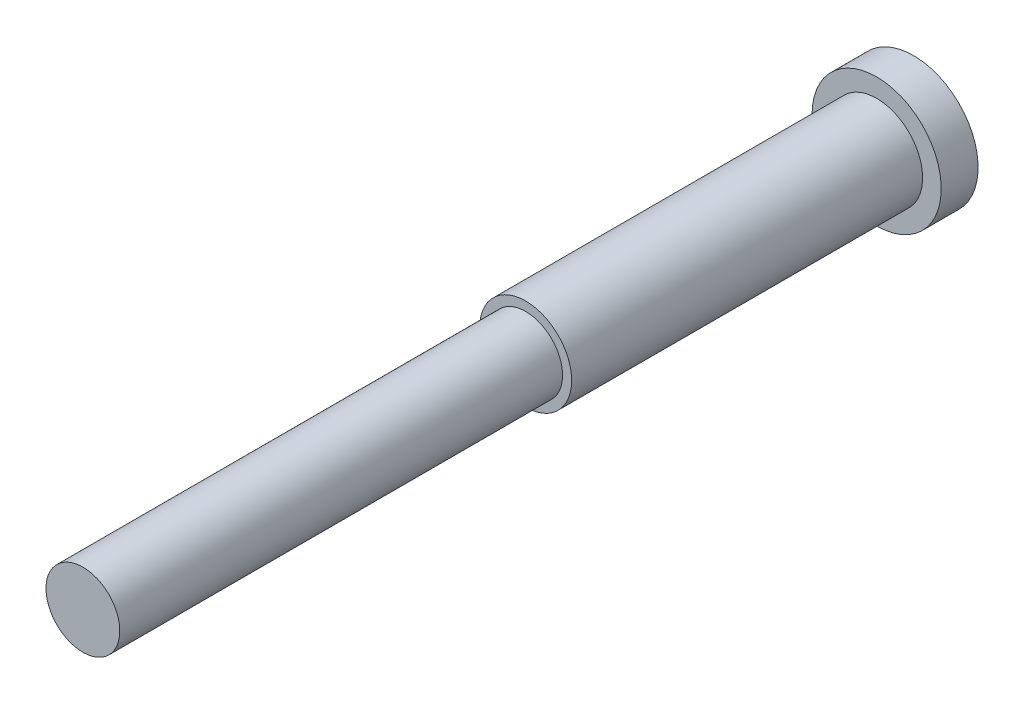
SolidWorks part; units mm, degrees
material "PW20:29:Sc:0:"
ref_plane "Front" through (0, 0, 0) normal (0, 0, 1) x (1, 0, 0)
ref_plane "Top" through (0, 0, 0) normal (0, 1, 0) x (1, 0, 0)
ref_plane "Right" through (0, 0, 0) normal (1, 0, 0) x (0, 0, -1)
other "Configuration Table"
sketch "Sketch1" plane through (0, 0, 0) normal (0, 0, 1) x (1, 0, 0)
  circle A0 centre (0, 0) radius 7.9121
  dimension "D1" = 15.8242
extrude "Base-Extrude" add sketch "Sketch1" along normal blind 60.4012
sketch "Sketch2" plane through (0, 0, 60.4012) normal (0, 0, 1) x (1, 0, 0)
  circle A0 centre (0, 0) radius 6.35
  dimension "D1" = 12.7
extrude "Boss-Extrude1" add sketch "Sketch2" along normal blind 76.2
sketch "Sketch3" plane through (0, 0, 0) normal (0, 0, -1) x (-1, 0, 0)
  circle A0 centre (0, 0) radius 11.1125
  dimension "D1" = 22.225
extrude "Boss-Extrude2" add sketch "Sketch3" along normal blind 6.35
ref_plane "Place" through (0, 0, 53.34) normal (0, 0, 1) x (1, 0, 0)
